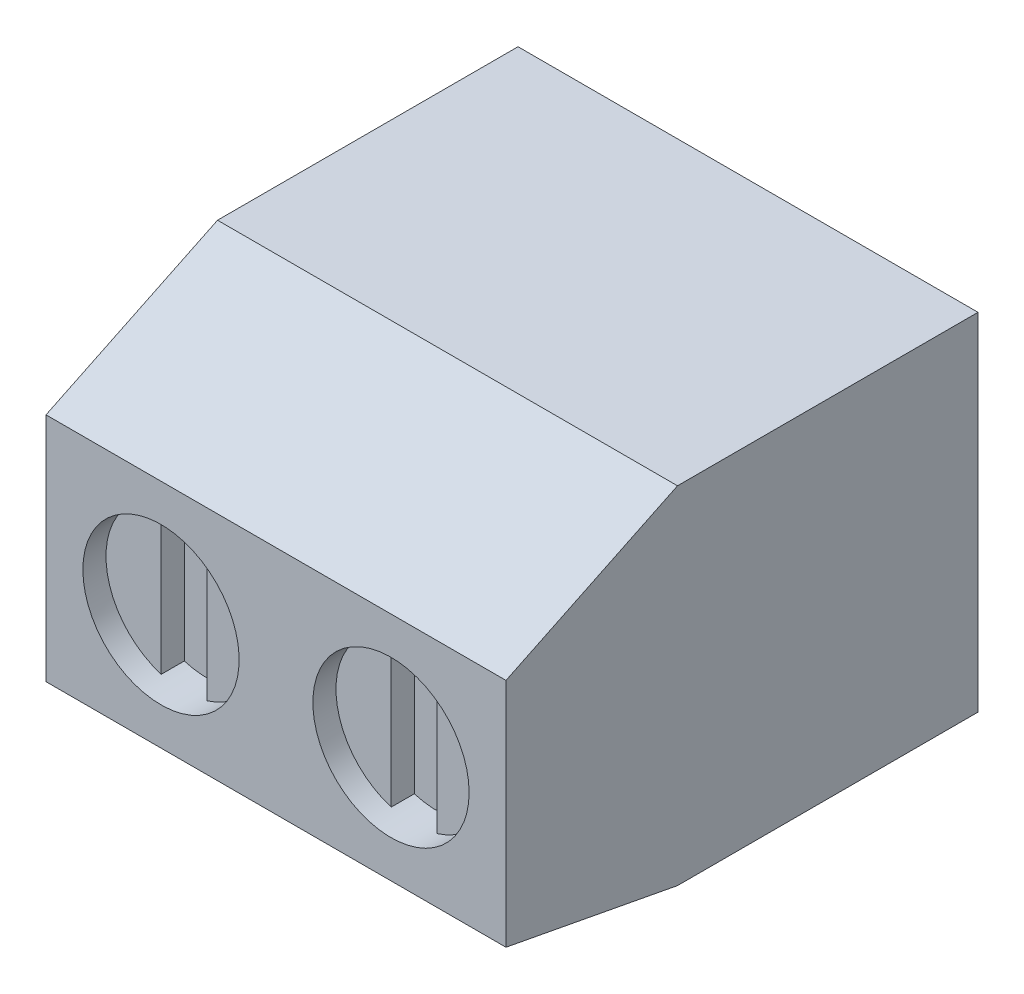
SolidWorks part; units mm, degrees
ref_plane "Alzado" through (0, 0, 0) normal (0, 0, 1) x (1, 0, 0)
ref_plane "Planta" through (0, 0, 0) normal (0, 1, 0) x (1, 0, 0)
ref_plane "Vista lateral" through (0, 0, 0) normal (1, 0, 0) x (0, 0, -1)
sketch "Croquis1" plane through (0, 0, 0) normal (0, 0, 1) x (1, 0, 0)
  line L1 (0, 0) -> (-9.95, 0)
  line L2 (0, 0) -> (0, 7.49)
  line L3 (0, 7.49) -> (-9.95, 7.49)
  line L4 (-9.95, 0) -> (-9.95, 7.49)
extrude "Saliente-Extruir1" add sketch "Croquis1" along normal blind 10.21
sketch "Croquis2" plane through (-9.95, 0, 0) normal (-1, 0, 0) x (0, 0, 1)
  line L0 (10.21, 5.6995) -> (10.21, 7.49)
  line L1 (10.21, 7.49) -> (6.5, 7.49)
  line L2 (10.21, 0.7) -> (10.21, 0)
  line L3 (10.21, 7.49) -> (10.21, 0) construction
  line L4 (10.21, 0) -> (6.5, 0)
  line L9 (10.21, 0) -> (0, 0) construction
  line L10 (6.5, 7.49) -> (10.21, 5.6995)
  line L11 (10.21, 0.7) -> (6.5, 0)
extrude "Cortar-Extruir1" cut sketch "Croquis2" against normal through all
sketch "Croquis3" plane through (0, 0, 0) normal (0, -1, 0) x (-1, 0, 0)
  line L1 (4.475, -1) -> (4.475, -6.08)
  line L3 (0.495, -6.08) -> (4.475, -6.08)
  line L4 (0.495, -1) -> (0.495, -6.08)
  line L5 (9.455, -1) -> (5.475, -1)
  line L6 (0.495, -1) -> (4.475, -1)
  line L8 (9.455, -1) -> (9.455, -6.08)
  line L11 (9.455, -6.08) -> (5.475, -6.08)
  line L12 (5.475, -1) -> (5.475, -6.08)
extrude "Cortar-Extruir3" cut sketch "Croquis3" against normal blind 1
sketch "Croquis4" plane through (0, 0, 10.21) normal (0, 0, 1) x (1, 0, 0)
  circle A0 centre (-2.4875, 3.1998) radius 1.69
  circle A1 centre (-7.4625, 3.1998) radius 1.69
extrude "Cortar-Extruir4" cut sketch "Croquis4" against normal blind 0.5
sketch "Croquis6" plane through (0, 0, 9.71) normal (0, 0, 1) x (1, 0, 0)
  line L2 (-6.967, 1.584) -> (-6.967, 4.8155)
  line L3 (-7.958, 1.584) -> (-7.958, 4.8155)
  line L4 (-1.992, 1.584) -> (-1.992, 4.8155)
  line L6 (-2.983, 1.584) -> (-2.983, 4.8155)
  arc A1 (-1.992, 4.8155) -> (-2.983, 4.8155) centre (-2.4875, 3.1998) ccw
  arc A2 (-2.983, 1.584) -> (-1.992, 1.584) centre (-2.4875, 3.1998) ccw
  arc A3 (-6.967, 1.584) -> (-7.958, 1.584) centre (-7.4625, 3.1998) cw
  arc A4 (-7.958, 4.8155) -> (-6.967, 4.8155) centre (-7.4625, 3.1998) cw
  point P8 (-2.4875, 1.5098)
  point P13 (-2.4875, 4.8898)
  point P17 (-7.4625, 4.8898)
  point P18 (-7.4625, 1.5098)
extrude "Cortar-Extruir6" cut sketch "Croquis6" against normal blind 0.5
sketch "Croquis7" plane through (0, 1, 0) normal (0, -1, 0) x (-1, 0, 0)
  line L4 (9.025, -2.2747) -> (5.905, -2.2747)
  line L5 (9.025, -2.2747) -> (9.025, -4.8053)
  line L6 (9.025, -4.8053) -> (5.905, -4.8053)
  line L7 (5.905, -2.2747) -> (5.905, -4.8053)
  line L8 (4.045, -2.2747) -> (4.045, -4.8053)
  line L9 (0.925, -4.8053) -> (4.045, -4.8053)
  line L10 (0.925, -2.2747) -> (0.925, -4.8053)
  line L11 (0.925, -2.2747) -> (4.045, -2.2747)
  point P6 (7.465, -3.54)
  point P13 (2.485, -3.54)
extrude "Cortar-Extruir7" cut sketch "Croquis7" against normal blind 2
